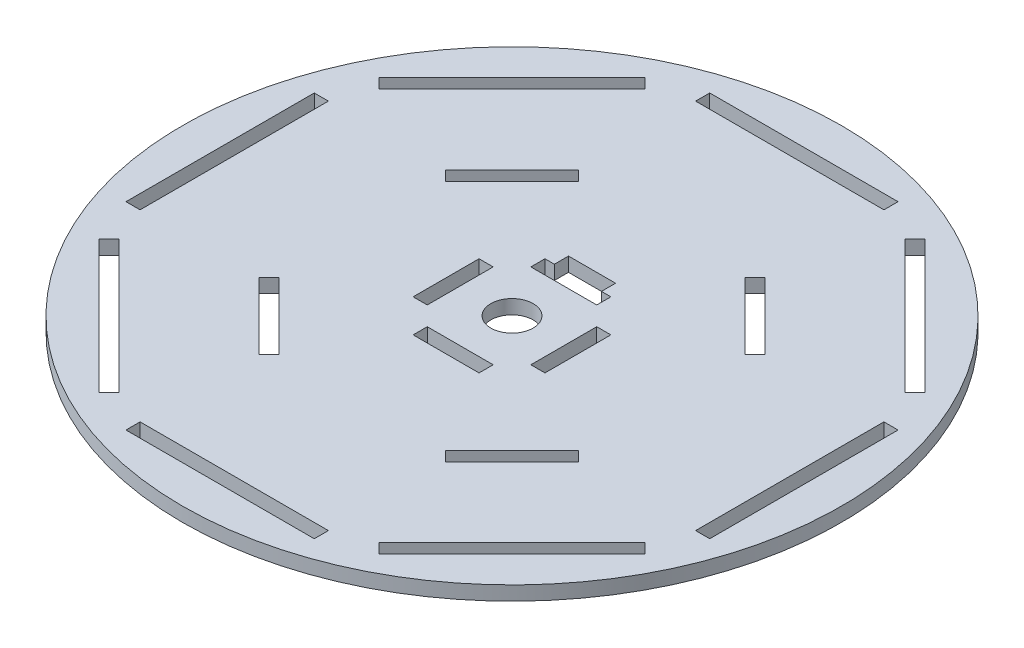
SolidWorks part; units mm, degrees
ref_plane "Alzado" through (0, 0, 0) normal (0, 0, 1) x (1, 0, 0)
ref_plane "Planta" through (0, 0, 0) normal (0, 1, 0) x (1, 0, 0)
ref_plane "Vista lateral" through (0, 0, 0) normal (1, 0, 0) x (0, 0, -1)
sketch "Croquis1" plane through (0, 0, 0) normal (0, 1, 0) x (1, 0, 0)
  line L0 (0, 11) -> (7, 11)
  line L1 (7, 11) -> (7, 14)
  line L2 (24.7487, 24.7487) -> (31.8198, 17.6777)
  line L3 (-7, 14) -> (-7, 11)
  line L4 (-7, 11) -> (0, 11)
  line L5 (11, 0) -> (11, 7)
  line L6 (11, 7) -> (14, 7)
  line L7 (14, 7) -> (14, -7)
  line L8 (14, -7) -> (11, -7)
  line L9 (11, -7) -> (11, 0)
  line L10 (0, 0) -> (-24.7487, 24.7487) construction
  line L11 (-24.7487, 24.7487) -> (-17.6777, 31.8198)
  line L12 (-17.6777, 31.8198) -> (-19.799, 33.9411)
  line L13 (-14, -7) -> (-11, -7)
  line L14 (-11, -7) -> (-11, 0)
  line L15 (-11, 0) -> (-11, 7)
  line L16 (-11, 7) -> (-14, 7)
  line L17 (-14, 7) -> (-14, -7)
  line L18 (7, -11) -> (7, -14)
  line L19 (0, -11) -> (7, -11)
  line L20 (7, -14) -> (-7, -14)
  line L21 (-7, -14) -> (-7, -11)
  line L22 (-7, -11) -> (0, -11)
  line L23 (-19.799, 33.9411) -> (-33.9411, 19.799)
  line L24 (-24.7487, 24.7487) -> (-31.8198, 17.6777)
  line L25 (-31.8198, 17.6777) -> (-33.9411, 19.799)
  line L26 (-7, 14) -> (-5, 14)
  line L27 (5, 14) -> (7, 14)
  line L28 (0, 17) -> (-5, 17)
  line L29 (-5, 17) -> (-5, 14)
  line L30 (0, 17) -> (5, 17)
  line L31 (31.8198, 17.6777) -> (33.9411, 19.799)
  line L32 (33.9411, 19.799) -> (19.799, 33.9411)
  line L33 (17.6777, 31.8198) -> (19.799, 33.9411)
  line L34 (24.7487, 24.7487) -> (17.6777, 31.8198)
  line L35 (24.7487, -24.7487) -> (17.6777, -31.8198)
  line L36 (17.6777, -31.8198) -> (19.799, -33.9411)
  line L37 (19.799, -33.9411) -> (33.9411, -19.799)
  line L38 (31.8198, -17.6777) -> (33.9411, -19.799)
  line L39 (24.7487, -24.7487) -> (31.8198, -17.6777)
  line L40 (-24.7487, -24.7487) -> (-31.8198, -17.6777)
  line L41 (0, 0) -> (0, 62) construction
  line L42 (0, 62) -> (20, 62)
  line L43 (20, 62) -> (20, 59)
  line L44 (20, 59) -> (-20, 59)
  line L45 (-20, 59) -> (-20, 62)
  line L46 (-20, 62) -> (0, 62)
  line L47 (55.8614, 27.5772) -> (27.5772, 55.8614)
  line L48 (27.5772, 55.8614) -> (29.6985, 57.9828)
  line L49 (29.6985, 57.9828) -> (43.8406, 43.8406)
  line L50 (43.8406, 43.8406) -> (57.9828, 29.6985)
  line L51 (57.9828, 29.6985) -> (55.8614, 27.5772)
  line L52 (59, -20) -> (59, 20)
  line L53 (59, 20) -> (62, 20)
  line L54 (62, 20) -> (62, 0)
  line L55 (62, 0) -> (62, -20)
  line L56 (62, -20) -> (59, -20)
  line L57 (27.5772, -55.8614) -> (55.8614, -27.5772)
  line L58 (55.8614, -27.5772) -> (57.9828, -29.6985)
  line L59 (57.9828, -29.6985) -> (43.8406, -43.8406)
  line L60 (43.8406, -43.8406) -> (29.6985, -57.9828)
  line L61 (29.6985, -57.9828) -> (27.5772, -55.8614)
  line L62 (-20, -59) -> (20, -59)
  line L63 (20, -59) -> (20, -62)
  line L64 (20, -62) -> (0, -62)
  line L65 (0, -62) -> (-20, -62)
  line L66 (-20, -62) -> (-20, -59)
  line L67 (-55.8614, -27.5772) -> (-27.5772, -55.8614)
  line L68 (-27.5772, -55.8614) -> (-29.6985, -57.9828)
  line L69 (-29.6985, -57.9828) -> (-43.8406, -43.8406)
  line L70 (-43.8406, -43.8406) -> (-57.9828, -29.6985)
  line L71 (-57.9828, -29.6985) -> (-55.8614, -27.5772)
  line L72 (-59, 20) -> (-59, -20)
  line L73 (-59, -20) -> (-62, -20)
  line L74 (-62, -20) -> (-62, 0)
  line L75 (-62, 0) -> (-62, 20)
  line L76 (-62, 20) -> (-59, 20)
  line L77 (-27.5772, 55.8614) -> (-55.8614, 27.5772)
  line L78 (-55.8614, 27.5772) -> (-57.9828, 29.6985)
  line L79 (-57.9828, 29.6985) -> (-43.8406, 43.8406)
  line L80 (-43.8406, 43.8406) -> (-29.6985, 57.9828)
  line L81 (-29.6985, 57.9828) -> (-27.5772, 55.8614)
  line L82 (-31.8198, -17.6777) -> (-33.9411, -19.799)
  line L83 (-33.9411, -19.799) -> (-19.799, -33.9411)
  line L84 (-17.6777, -31.8198) -> (-19.799, -33.9411)
  line L85 (-24.7487, -24.7487) -> (-17.6777, -31.8198)
  line L86 (5, 17) -> (5, 14)
  circle A0 centre (0, 0) radius 4.5
  circle A2 centre (0, 0) radius 70
  point P47 (0, 0)
  point P88 (0, 0)
  point P93 (0, 0)
  dimension "D1" = 9
  dimension "D2" = 14
  dimension "D3" = 140
  dimension "D4" = 7
  dimension "D5" = 3
  dimension "D6" = 14
  dimension "D7" = 35
  dimension "D8" = 3
  dimension "D9" = 10
  dimension "D10" = 3
  dimension "D11" = 20
  dimension "D12" = 10
  dimension "D14" = 62
  dimension "D15" = 20
  dimension "D16" = 3
  dimension "D17" = 40
  dimension "D19" = 3
  dimension "D13" = 4
  dimension "D20" = 5
  dimension "D21" = 3
  dimension "D22" = 5
  dimension "D18" = 8
extrude "Saliente-Extruir1" add sketch "Croquis1" along normal blind 3
